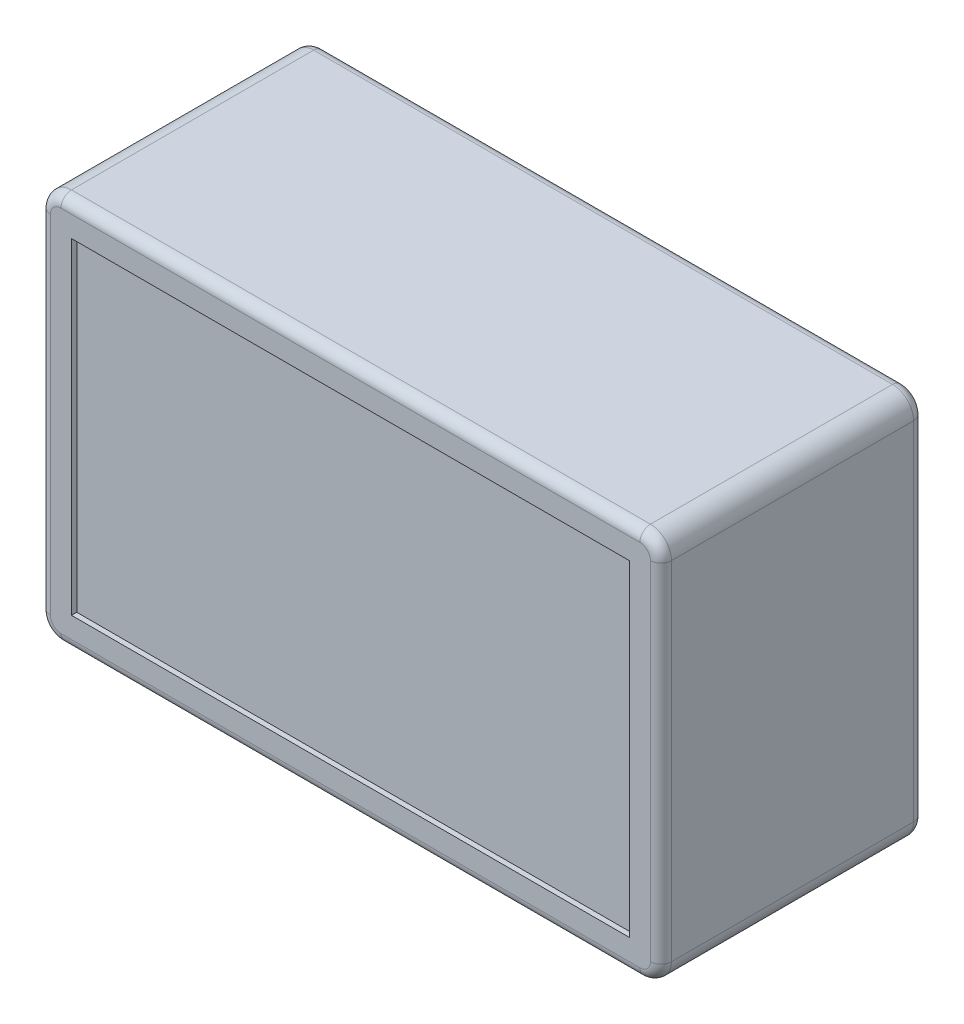
SolidWorks part; units mm, degrees
ref_plane "Front Plane" through (0, 0, 0) normal (0, 0, 1) x (1, 0, 0)
ref_plane "Top Plane" through (0, 0, 0) normal (0, 1, 0) x (1, 0, 0)
ref_plane "Right Plane" through (0, 0, 0) normal (1, 0, 0) x (0, 0, -1)
sketch "Sketch1" plane through (0, 0, 0) normal (0, 0, 1) x (1, 0, 0)
  line L0 (0, 25) -> (0, 97.309) construction
  line L1 (-29.5, 82) -> (29.5, 82)
  line L2 (-29.5, 82) -> (-29.5, 45)
  line L3 (-29.5, 45) -> (29.5, 45)
  line L4 (29.5, 82) -> (29.5, 45)
  dimension "D1" = 59
  dimension "D2" = 37
  dimension "D3" = 29.5
extrude "Boss-Extrude1" add sketch "Sketch1" along normal mid plane 25
sketch "Sketch2" plane through (0, 0, -12.5) normal (0, 0, -1) x (-1, 0, 0)
  line L0 (29.5, 63.5) -> (-29.5, 63.5) construction
  line L1 (29.5, 82) -> (29.5, 45) construction
  line L2 (-29.5, 45) -> (-29.5, 82) construction
  circle A0 centre (14.5, 66.5) radius 7
extrude "Boss-Extrude2" add sketch "Sketch2" along normal blind 3
fillet "Fillet1" radius 2 4 edges at (29.5, 45, 0) (29.5, 82, 0) (-29.5, 45, 0) (-29.5, 82, 0)
sketch "Sketch3" plane through (0, 0, -12.5) normal (0, 0, -1) x (-1, 0, 0)
  line L1 (5.5, 78.5) -> (23.5, 78.5)
  line L2 (2.5, 75.5) -> (2.5, 57.5)
  line L3 (5.5, 54.5) -> (23.5, 54.5)
  line L4 (26.5, 75.5) -> (26.5, 57.5)
  circle A0 centre (14.5, 66.5) radius 7 construction
  arc A1 (23.5, 78.5) -> (26.5, 75.5) centre (23.5, 75.5) cw
  arc A2 (23.5, 54.5) -> (26.5, 57.5) centre (23.5, 57.5) ccw
  arc A3 (2.5, 57.5) -> (5.5, 54.5) centre (5.5, 57.5) ccw
  arc A4 (5.5, 78.5) -> (2.5, 75.5) centre (5.5, 75.5) ccw
  point P8 (26.5, 78.5)
  point P11 (26.5, 54.5)
  point P16 (2.5, 78.5)
  dimension "D5" = 3
  dimension "D1" = 12
  dimension "D2" = 24
  dimension "D3" = 24
  dimension "D4" = 12
extrude "Boss-Extrude3" add sketch "Sketch3" along normal mid plane 2
sketch "Sketch4" plane through (0, 0, -15.5) normal (0, 0, -1) x (-1, 0, 0)
  circle A0 centre (14.5, 66.5) radius 6
extrude "Cut-Extrude1" cut sketch "Sketch4" against normal blind 0.5
sketch "Sketch5" plane through (0, 0, -12.5) normal (0, 0, -1) x (-1, 0, 0)
  line L0 (-29.5, 63.5) -> (29.5, 63.5) construction
  line L1 (-29.5, 47) -> (-29.5, 80) construction
  line L2 (29.5, 80) -> (29.5, 47) construction
  circle A0 centre (-17.5, 63.5) radius 5
  dimension "D1" = 10
  dimension "D2" = 12
extrude "Boss-Extrude4" add sketch "Sketch5" along normal blind 2
fillet "Fillet2" radius 1 16 edges at (28.9142, 81.4142, 12.5) (29.5, 63.5, 12.5) (28.9142, 45.5858, 12.5) (0, 45, 12.5) (-28.9142, 45.5858, 12.5) (-29.5, 63.5, 12.5) (-28.9142, 81.4142, 12.5) (28.9142, 81.4142, -12.5) (29.5, 63.5, -12.5) (28.9142, 45.5858, -12.5) (0, 45, -12.5) (-28.9142, 45.5858, -12.5) (-29.5, 63.5, -12.5) (-28.9142, 81.4142, -12.5) (0, 82, 12.5) (0, 82, -12.5)
sketch "Sketch6" plane through (0, 0, 12.5) normal (0, 0, 1) x (1, 0, 0)
  line L8 (26.5, 48) -> (26.5, 79)
  line L9 (26.5, 79) -> (-26.5, 79)
  line L10 (-26.5, 79) -> (-26.5, 48)
  line L11 (-26.5, 48) -> (26.5, 48)
  line L12 (26.5, 48) -> (26.5, 79)
  line L13 (26.5, 79) -> (-26.5, 79)
  line L14 (-26.5, 79) -> (-26.5, 48)
  line L15 (-26.5, 48) -> (26.5, 48)
  dimension "D1" = 2
extrude "Cut-Extrude2" cut sketch "Sketch6" against normal blind 0.5
